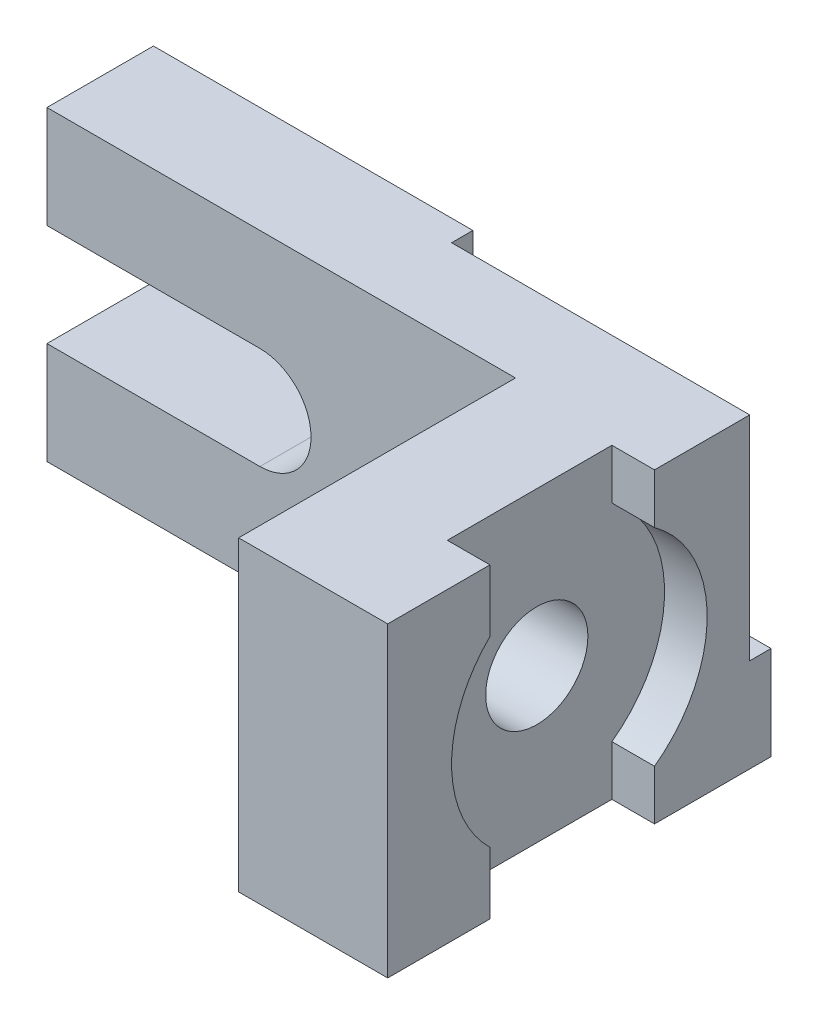
SolidWorks part; units mm, degrees
ref_plane "Front Plane" through (0, 0, 0) normal (1, 0, 0) x (0, 1, 0)
ref_plane "Top Plane" through (0, 0, 0) normal (0, 0, 1) x (0, 1, 0)
ref_plane "Right Plane" through (0, 0, 0) normal (0, 1, 0) x (-1, 0, 0)
sketch "Sketch1" plane through (0, 0, 0) normal (0, 1, 0) x (-1, 0, 0)
  line L0 (0, 0) -> (145, 0)
  line L1 (145, 0) -> (145, 25)
  line L2 (145, 25) -> (35, 25)
  line L3 (35, 25) -> (35, 90)
  line L4 (35, 90) -> (0, 90)
  line L5 (0, 90) -> (0, 0)
  dimension "D1" = 90
  dimension "D2" = 145
  dimension "D3" = 25
  dimension "D4" = 35
extrude "Boss-Extrude1" add sketch "Sketch1" along normal mid plane 72
sketch "Sketch2" plane through (0, 0, 0) normal (1, 0, 0) x (0, 1, 0)
  line L0 (36, 0) -> (-36, 0) construction
  line L1 (-36, 90) -> (-36, 0) construction
  circle A0 centre (0, 45) radius 30
  dimension "D1" = 60
  dimension "D2" = 45
  dimension "D3" = 36
extrude "Cut-Extrude1" cut sketch "Sketch2" against normal blind 10 and the other way through all
sketch "Sketch3" plane through (0, 0, 0) normal (1, 0, 0) x (0, 1, 0)
  line L0 (36, 90) -> (36, 0) construction
  line L1 (-36, 66) -> (36, 66)
  line L2 (-36, 66) -> (-36, 27.3609)
  line L3 (-36, 27.3609) -> (36, 27.3609)
  line L4 (36, 66) -> (36, 27.3609)
  line L5 (36, 90) -> (-36, 90) construction
  line L7 (36, 0) -> (-36, 0) construction
  point P0 (0, 45)
  dimension "D1" = 27.3609
  dimension "D2" = 24
extrude "Cut-Extrude2" cut sketch "Sketch3" against normal blind 10
sketch "Sketch4" plane through (-10, 0, 0) normal (1, 0, 0) x (0, 1, 0)
  circle A0 centre (0, 45) radius 12
  dimension "D1" = 24
extrude "Cut-Extrude3" cut sketch "Sketch4" against normal through all
sketch "Sketch5" plane through (0, 0, 0) normal (1, 0, 0) x (0, 1, 0)
  line L0 (36, 0) -> (36, 5)
  line L1 (36, 27.3609) -> (36, 0) construction
  line L2 (36, 5) -> (-14, 5)
  line L3 (-14, 5) -> (-14, 0)
  line L4 (36, 0) -> (-36, 0) construction
  line L5 (-14, 0) -> (36, 0)
  dimension "D1" = 50
  dimension "D2" = 5
extrude "Cut-Extrude4" cut sketch "Sketch5" against normal blind 70
sketch "Sketch6" plane through (0, 0, 25) normal (0, 0, 1) x (1, 0, 0)
  line L0 (-95, 12) -> (-145, 12)
  line L1 (-145, 36) -> (-145, -36) construction
  line L2 (-95, -12) -> (-145, -12)
  line L4 (-145, 12) -> (-145, -12)
  line L5 (-18.4262, 0) -> (16.8116, 0) construction
  arc A0 (-95, -12) -> (-95, 12) centre (-95, 0) ccw
  dimension "D1" = 24
  dimension "D2" = 50
extrude "Cut-Extrude5" cut sketch "Sketch6" against normal blind 70
